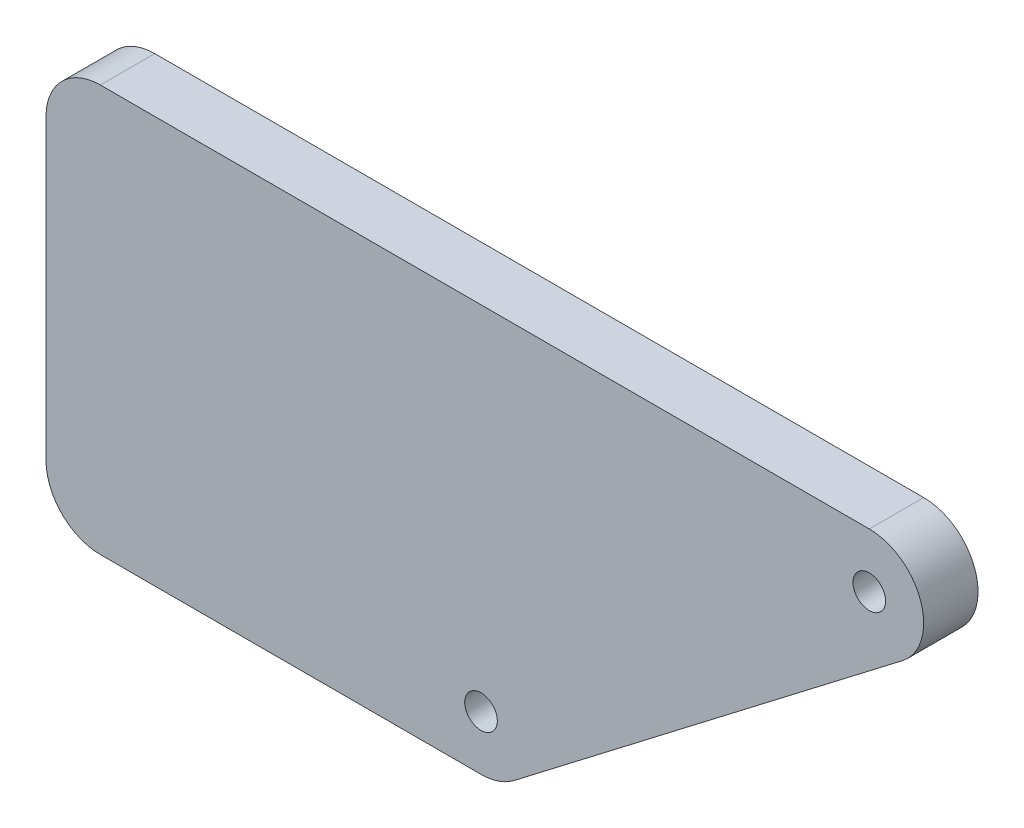
SolidWorks part; units mm, degrees
ref_plane "前视基准面" through (0, 0, 0) normal (0, 0, 1) x (1, 0, 0)
ref_plane "上视基准面" through (0, 0, 0) normal (0, 1, 0) x (1, 0, 0)
ref_plane "右视基准面" through (0, 0, 0) normal (1, 0, 0) x (0, 0, -1)
sketch "Sketch1" plane through (0, 0, 0) normal (0, 0, 1) x (1, 0, 0)
  line L0 (122.9511, -18.8201) -> (93.1268, -73.5554)
  line L1 (93.1268, -73.5554) -> (122.7846, -133.2618)
  line L2 (122.7846, -133.2618) -> (122.9511, -18.8201)
  line L3 (0, 0) -> (71.4018, 54.7885)
  line L4 (71.4018, 54.7885) -> (-333.3333, 54.7885)
  line L5 (-333.3333, 54.7885) -> (0, 0)
  line L6 (0, 0) -> (-333.3333, 54.7885)
  line L7 (-333.3333, 54.7885) -> (-333.3333, 0)
  line L8 (-333.3333, 0) -> (0, 0)
  line L9 (71.4018, 54.7885) -> (122.9511, -18.8201)
  line L10 (122.9511, -18.8201) -> (94.2741, 2.9429)
  line L11 (94.2741, 2.9429) -> (71.4018, 54.7885)
  line L12 (71.4018, 54.7885) -> (94.2741, 2.9429)
  line L13 (94.2741, 2.9429) -> (71.4018, 54.7885)
  line L14 (94.2741, 2.9429) -> (18.6205, -18.6205)
  line L15 (18.6205, -18.6205) -> (37.467, -41.2946)
  line L16 (37.467, -41.2946) -> (94.2741, 2.9429)
  line L17 (94.2741, 2.9429) -> (37.467, -41.2946)
  line L18 (37.467, -41.2946) -> (94.2741, 2.9429)
  line L19 (184.818, -172.2512) -> (184.6311, -172.3314)
  line L20 (184.6311, -172.3314) -> (184.444, -172.4113)
  line L21 (184.444, -172.4113) -> (184.2569, -172.4911)
  line L22 (184.2569, -172.4911) -> (184.0696, -172.5706)
  line L23 (184.0696, -172.5706) -> (183.8823, -172.6498)
  line L24 (183.8823, -172.6498) -> (183.6948, -172.7288)
  line L25 (183.6948, -172.7288) -> (183.5072, -172.8076)
  line L26 (183.5072, -172.8076) -> (183.3195, -172.8862)
  line L27 (183.3195, -172.8862) -> (183.1318, -172.9645)
  line L28 (183.1318, -172.9645) -> (182.9439, -173.0426)
  line L29 (182.9439, -173.0426) -> (182.7559, -173.1204)
  line L30 (182.7559, -173.1204) -> (182.5679, -173.198)
  line L31 (182.5679, -173.198) -> (182.3797, -173.2753)
  line L32 (182.3797, -173.2753) -> (182.1914, -173.3524)
  line L33 (182.1914, -173.3524) -> (182.003, -173.4293)
  line L34 (182.003, -173.4293) -> (181.8146, -173.5059)
  line L35 (181.8146, -173.5059) -> (181.626, -173.5823)
  line L36 (181.626, -173.5823) -> (181.4374, -173.6584)
  line L37 (181.4374, -173.6584) -> (181.2486, -173.7343)
  line L38 (181.2486, -173.7343) -> (181.0598, -173.8099)
  line L39 (181.0598, -173.8099) -> (180.8709, -173.8853)
  line L40 (180.8709, -173.8853) -> (180.6819, -173.9604)
  line L41 (180.6819, -173.9604) -> (180.4928, -174.0353)
  line L42 (180.4928, -174.0353) -> (180.3036, -174.11)
  line L43 (180.3036, -174.11) -> (180.1143, -174.1843)
  line L44 (180.1143, -174.1843) -> (179.9249, -174.2585)
  line L45 (179.9249, -174.2585) -> (179.7355, -174.3324)
  line L46 (179.7355, -174.3324) -> (179.546, -174.406)
  line L47 (179.546, -174.406) -> (179.3564, -174.4794)
  line L48 (179.3564, -174.4794) -> (179.1667, -174.5525)
  line L49 (179.1667, -174.5525) -> (178.9769, -174.6254)
  line L50 (178.9769, -174.6254) -> (178.7871, -174.698)
  line L51 (178.7871, -174.698) -> (178.5972, -174.7704)
  line L52 (178.5972, -174.7704) -> (178.4072, -174.8425)
  line L53 (178.4072, -174.8425) -> (178.2172, -174.9143)
  line L54 (178.2172, -174.9143) -> (178.027, -174.9859)
  line L55 (178.027, -174.9859) -> (177.8368, -175.0573)
  line L56 (177.8368, -175.0573) -> (177.6466, -175.1283)
  line L57 (177.6466, -175.1283) -> (177.4563, -175.1992)
  line L58 (177.4563, -175.1992) -> (177.2659, -175.2697)
  line L59 (177.2659, -175.2697) -> (177.0754, -175.34)
  line L60 (177.0754, -175.34) -> (176.8849, -175.41)
  line L61 (176.8849, -175.41) -> (176.6943, -175.4798)
  line L62 (176.6943, -175.4798) -> (176.5037, -175.5493)
  line L63 (176.5037, -175.5493) -> (176.313, -175.6186)
  line L64 (176.313, -175.6186) -> (176.1223, -175.6875)
  line L65 (176.1223, -175.6875) -> (175.9315, -175.7562)
  line L66 (175.9315, -175.7562) -> (175.7407, -175.8247)
  line L67 (175.7407, -175.8247) -> (175.5498, -175.8928)
  line L68 (175.5498, -175.8928) -> (175.3588, -175.9608)
  line L69 (175.3588, -175.9608) -> (175.1679, -176.0284)
  line L70 (175.1679, -176.0284) -> (174.9768, -176.0958)
  line L71 (174.9768, -176.0958) -> (174.7858, -176.1629)
  line L72 (174.7858, -176.1629) -> (174.5947, -176.2297)
  line L73 (174.5947, -176.2297) -> (174.4036, -176.2962)
  line L74 (174.4036, -176.2962) -> (174.2124, -176.3625)
  line L75 (174.2124, -176.3625) -> (174.0212, -176.4285)
  line L76 (174.0212, -176.4285) -> (173.8299, -176.4943)
  line L77 (173.8299, -176.4943) -> (173.6387, -176.5597)
  line L78 (173.6387, -176.5597) -> (173.4474, -176.6249)
  line L79 (173.4474, -176.6249) -> (173.2561, -176.6898)
  line L80 (173.2561, -176.6898) -> (173.0648, -176.7545)
  line L81 (173.0648, -176.7545) -> (172.8734, -176.8188)
  line L82 (172.8734, -176.8188) -> (172.682, -176.8829)
  line L83 (172.682, -176.8829) -> (172.4906, -176.9467)
  line L84 (172.4906, -176.9467) -> (172.2992, -177.0102)
  line L85 (172.2992, -177.0102) -> (172.1078, -177.0735)
  line L86 (172.1078, -177.0735) -> (171.9164, -177.1365)
  line L87 (171.9164, -177.1365) -> (171.725, -177.1991)
  line L88 (171.725, -177.1991) -> (171.5335, -177.2616)
  line L89 (171.5335, -177.2616) -> (171.3421, -177.3237)
  line L90 (171.3421, -177.3237) -> (171.1507, -177.3855)
  line L91 (171.1507, -177.3855) -> (170.9592, -177.4471)
  line L92 (170.9592, -177.4471) -> (170.7678, -177.5083)
  line L93 (170.7678, -177.5083) -> (170.5764, -177.5693)
  line L94 (170.5764, -177.5693) -> (170.385, -177.63)
  line L95 (170.385, -177.63) -> (170.1936, -177.6905)
  line L96 (170.1936, -177.6905) -> (170.0022, -177.7506)
  line L97 (170.0022, -177.7506) -> (169.8108, -177.8104)
  line L98 (169.8108, -177.8104) -> (169.6194, -177.87)
  line L99 (169.6194, -177.87) -> (169.4281, -177.9293)
  line L100 (169.4281, -177.9293) -> (169.2368, -177.9883)
  line L101 (169.2368, -177.9883) -> (169.0455, -178.047)
  line L102 (169.0455, -178.047) -> (168.8543, -178.1054)
  line L103 (168.8543, -178.1054) -> (168.6631, -178.1635)
  line L104 (168.6631, -178.1635) -> (168.4719, -178.2213)
  line L105 (168.4719, -178.2213) -> (168.2807, -178.2789)
  line L106 (168.2807, -178.2789) -> (168.0896, -178.3361)
  line L107 (168.0896, -178.3361) -> (167.8985, -178.3931)
  line L108 (167.8985, -178.3931) -> (167.7075, -178.4497)
  line L109 (167.7075, -178.4497) -> (167.5165, -178.5061)
  line L110 (167.5165, -178.5061) -> (167.3256, -178.5622)
  line L111 (167.3256, -178.5622) -> (167.1347, -178.618)
  line L112 (167.1347, -178.618) -> (166.9439, -178.6735)
  line L113 (166.9439, -178.6735) -> (166.7531, -178.7287)
  line L114 (166.7531, -178.7287) -> (166.5624, -178.7836)
  line L115 (166.5624, -178.7836) -> (166.3718, -178.8382)
  line L116 (166.3718, -178.8382) -> (166.1812, -178.8925)
  line L117 (166.1812, -178.8925) -> (165.9907, -178.9465)
  line L118 (165.9907, -178.9465) -> (165.8003, -179.0002)
  line L119 (165.8003, -179.0002) -> (165.6099, -179.0537)
  line L120 (165.6099, -179.0537) -> (165.4196, -179.1068)
  line L121 (165.4196, -179.1068) -> (165.2294, -179.1596)
  line L122 (165.2294, -179.1596) -> (165.0393, -179.2122)
  line L123 (165.0393, -179.2122) -> (164.8492, -179.2644)
  line L124 (164.8492, -179.2644) -> (164.6593, -179.3164)
  line L125 (164.6593, -179.3164) -> (164.4694, -179.368)
  line L126 (164.4694, -179.368) -> (164.2796, -179.4193)
  line L127 (164.2796, -179.4193) -> (164.09, -179.4704)
  line L128 (164.09, -179.4704) -> (163.9004, -179.5211)
  line L129 (163.9004, -179.5211) -> (163.7109, -179.5716)
  line L130 (163.7109, -179.5716) -> (163.5215, -179.6218)
  line L131 (163.5215, -179.6218) -> (163.3323, -179.6716)
  line L132 (163.3323, -179.6716) -> (163.1431, -179.7212)
  line L133 (163.1431, -179.7212) -> (162.9541, -179.7704)
  line L134 (162.9541, -179.7704) -> (162.7651, -179.8194)
  line L135 (162.7651, -179.8194) -> (162.5763, -179.868)
  line L136 (162.5763, -179.868) -> (162.3877, -179.9164)
  line L137 (162.3877, -179.9164) -> (162.1991, -179.9644)
  line L138 (162.1991, -179.9644) -> (162.0107, -180.0122)
  line L139 (162.0107, -180.0122) -> (161.8224, -180.0596)
  line L140 (161.8224, -180.0596) -> (161.6342, -180.1068)
  line L141 (161.6342, -180.1068) -> (161.4462, -180.1536)
  line L142 (161.4462, -180.1536) -> (161.2583, -180.2002)
  line L143 (161.2583, -180.2002) -> (161.0705, -180.2464)
  line L144 (161.0705, -180.2464) -> (160.8829, -180.2924)
  line L145 (160.8829, -180.2924) -> (160.6955, -180.338)
  line L146 (160.6955, -180.338) -> (160.5082, -180.3834)
  line L147 (160.5082, -180.3834) -> (160.321, -180.4284)
  line L148 (160.321, -180.4284) -> (160.134, -180.4732)
  line L149 (160.134, -180.4732) -> (159.9472, -180.5176)
  line L150 (159.9472, -180.5176) -> (159.7605, -180.5617)
  line L151 (159.7605, -180.5617) -> (159.574, -180.6056)
  line L152 (159.574, -180.6056) -> (159.3877, -180.6491)
  line L153 (159.3877, -180.6491) -> (159.2015, -180.6924)
  line L154 (159.2015, -180.6924) -> (159.0156, -180.7353)
  line L155 (159.0156, -180.7353) -> (158.8298, -180.7779)
  line L156 (158.8298, -180.7779) -> (158.6441, -180.8203)
  line L157 (158.6441, -180.8203) -> (158.4587, -180.8623)
  line L158 (158.4587, -180.8623) -> (158.2735, -180.904)
  line L159 (158.2735, -180.904) -> (158.0884, -180.9455)
  line L160 (158.0884, -180.9455) -> (157.9035, -180.9866)
  line L161 (157.9035, -180.9866) -> (157.7189, -181.0274)
  line L162 (157.7189, -181.0274) -> (157.5344, -181.068)
  line L163 (157.5344, -181.068) -> (157.3502, -181.1082)
  line L164 (157.3502, -181.1082) -> (157.1661, -181.1481)
  line L165 (157.1661, -181.1481) -> (156.9823, -181.1878)
  line L166 (156.9823, -181.1878) -> (156.7986, -181.2271)
  line L167 (156.7986, -181.2271) -> (156.6152, -181.2662)
  line L168 (156.6152, -181.2662) -> (156.432, -181.3049)
  line L169 (156.432, -181.3049) -> (156.249, -181.3433)
  line L170 (156.249, -181.3433) -> (156.0663, -181.3815)
  line L171 (156.0663, -181.3815) -> (155.8838, -181.4193)
  line L172 (155.8838, -181.4193) -> (155.7015, -181.4569)
  line L173 (155.7015, -181.4569) -> (155.5194, -181.4941)
  line L174 (155.5194, -181.4941) -> (155.3376, -181.5311)
  line L175 (155.3376, -181.5311) -> (155.156, -181.5678)
  line L176 (155.156, -181.5678) -> (154.9747, -181.6041)
  line L177 (154.9747, -181.6041) -> (154.7936, -181.6402)
  line L178 (154.7936, -181.6402) -> (154.6127, -181.676)
  line L179 (154.6127, -181.676) -> (154.4322, -181.7114)
  line L180 (154.4322, -181.7114) -> (154.2518, -181.7466)
  line L181 (154.2518, -181.7466) -> (154.0718, -181.7815)
  line L182 (154.0718, -181.7815) -> (153.892, -181.8161)
  line L183 (153.892, -181.8161) -> (153.7124, -181.8504)
  line L184 (153.7124, -181.8504) -> (153.5331, -181.8844)
  line L185 (153.5331, -181.8844) -> (153.3541, -181.9181)
  line L186 (153.3541, -181.9181) -> (153.1754, -181.9516)
  line L187 (153.1754, -181.9516) -> (152.9969, -181.9847)
  line L188 (152.9969, -181.9847) -> (152.8188, -182.0176)
  line L189 (152.8188, -182.0176) -> (152.6409, -182.0501)
  line L190 (152.6409, -182.0501) -> (152.4633, -182.0824)
  line L191 (152.4633, -182.0824) -> (152.286, -182.1144)
  line L192 (152.286, -182.1144) -> (152.109, -182.1461)
  line L193 (152.109, -182.1461) -> (151.9322, -182.1775)
  line L194 (151.9322, -182.1775) -> (151.7558, -182.2086)
  line L195 (151.7558, -182.2086) -> (151.5797, -182.2394)
  line L196 (151.5797, -182.2394) -> (151.4039, -182.27)
  line L197 (151.4039, -182.27) -> (151.2284, -182.3002)
  line L198 (151.2284, -182.3002) -> (151.0532, -182.3302)
  line L199 (151.0532, -182.3302) -> (150.8783, -182.3599)
  line L200 (150.8783, -182.3599) -> (150.7037, -182.3893)
  line L201 (150.7037, -182.3893) -> (150.5295, -182.4184)
  line L202 (150.5295, -182.4184) -> (150.3555, -182.4473)
  line L203 (150.3555, -182.4473) -> (150.1819, -182.4758)
  line L204 (150.1819, -182.4758) -> (150.0087, -182.5041)
  line L205 (150.0087, -182.5041) -> (149.8357, -182.5321)
  line L206 (149.8357, -182.5321) -> (149.6631, -182.5598)
  line L207 (149.6631, -182.5598) -> (149.4908, -182.5873)
  line L208 (149.4908, -182.5873) -> (149.3189, -182.6145)
  line L209 (149.3189, -182.6145) -> (149.1473, -182.6413)
  line L210 (149.1473, -182.6413) -> (148.9761, -182.668)
  line L211 (148.9761, -182.668) -> (148.8052, -182.6943)
  line L212 (148.8052, -182.6943) -> (148.6347, -182.7204)
  line L213 (148.6347, -182.7204) -> (148.4645, -182.7462)
  line L214 (148.4645, -182.7462) -> (148.2946, -182.7717)
  line L215 (148.2946, -182.7717) -> (148.1252, -182.797)
  line L216 (148.1252, -182.797) -> (147.9561, -182.8219)
  line L217 (147.9561, -182.8219) -> (147.7873, -182.8467)
  line L218 (147.7873, -182.8467) -> (147.619, -182.8711)
  line L219 (147.619, -182.8711) -> (147.451, -182.8953)
  line L220 (147.451, -182.8953) -> (147.2833, -182.9192)
  line L221 (147.2833, -182.9192) -> (147.1161, -182.9429)
  line L222 (147.1161, -182.9429) -> (146.9492, -182.9662)
  line L223 (146.9492, -182.9662) -> (146.7827, -182.9894)
  line L224 (146.7827, -182.9894) -> (146.6166, -183.0122)
  line L225 (146.6166, -183.0122) -> (146.4509, -183.0348)
  line L226 (146.4509, -183.0348) -> (146.2856, -183.0571)
  line L227 (146.2856, -183.0571) -> (146.1206, -183.0792)
  line L228 (146.1206, -183.0792) -> (145.9561, -183.101)
  line L229 (145.9561, -183.101) -> (145.7919, -183.1226)
  line L230 (145.7919, -183.1226) -> (145.6282, -183.1439)
  line L231 (145.6282, -183.1439) -> (145.4649, -183.165)
  line L232 (145.4649, -183.165) -> (145.3019, -183.1858)
  line L233 (145.3019, -183.1858) -> (145.1394, -183.2063)
  line L234 (145.1394, -183.2063) -> (144.9773, -183.2266)
  line L235 (144.9773, -183.2266) -> (144.8156, -183.2466)
  line L236 (144.8156, -183.2466) -> (144.6543, -183.2664)
  line L237 (144.6543, -183.2664) -> (144.4934, -183.286)
  line L238 (144.4934, -183.286) -> (144.3329, -183.3053)
  line L239 (144.3329, -183.3053) -> (144.1729, -183.3243)
  line L240 (144.1729, -183.3243) -> (144.0133, -183.3431)
  line L241 (144.0133, -183.3431) -> (143.8541, -183.3617)
  line L242 (143.8541, -183.3617) -> (143.6953, -183.38)
  line L243 (143.6953, -183.38) -> (143.537, -183.3981)
  line L244 (143.537, -183.3981) -> (143.3791, -183.4159)
  line L245 (143.3791, -183.4159) -> (143.2217, -183.4335)
  line L246 (143.2217, -183.4335) -> (143.0646, -183.4508)
  line L247 (143.0646, -183.4508) -> (142.908, -183.468)
  line L248 (142.908, -183.468) -> (142.7519, -183.4849)
  line L249 (142.7519, -183.4849) -> (142.5962, -183.5015)
  line L250 (142.5962, -183.5015) -> (142.4409, -183.5179)
  line L251 (142.4409, -183.5179) -> (142.2861, -183.5341)
  line L252 (142.2861, -183.5341) -> (142.1318, -183.5501)
  line L253 (142.1318, -183.5501) -> (141.9778, -183.5658)
  line L254 (141.9778, -183.5658) -> (141.8244, -183.5813)
  line L255 (141.8244, -183.5813) -> (141.6714, -183.5966)
  line L256 (141.6714, -183.5966) -> (141.5188, -183.6116)
  line L257 (141.5188, -183.6116) -> (141.3667, -183.6265)
  line L258 (141.3667, -183.6265) -> (141.2151, -183.6411)
  line L259 (141.2151, -183.6411) -> (141.0639, -183.6554)
  line L260 (141.0639, -183.6554) -> (140.9132, -183.6696)
  line L261 (140.9132, -183.6696) -> (140.7629, -183.6836)
  line L262 (140.7629, -183.6836) -> (140.6132, -183.6973)
  line L263 (140.6132, -183.6973) -> (140.4638, -183.7108)
  line L264 (140.4638, -183.7108) -> (140.315, -183.7241)
  line L265 (140.315, -183.7241) -> (140.1666, -183.7372)
  line L266 (140.1666, -183.7372) -> (140.0187, -183.7501)
  line L267 (140.0187, -183.7501) -> (139.8713, -183.7627)
  line L268 (139.8713, -183.7627) -> (139.7243, -183.7752)
  line L269 (139.7243, -183.7752) -> (139.5778, -183.7874)
  line L270 (139.5778, -183.7874) -> (139.4318, -183.7995)
  line L271 (139.4318, -183.7995) -> (139.2863, -183.8113)
  line L272 (139.2863, -183.8113) -> (139.1412, -183.823)
  line L273 (139.1412, -183.823) -> (138.9966, -183.8344)
  line L274 (138.9966, -183.8344) -> (138.8525, -183.8456)
  line L275 (138.8525, -183.8456) -> (138.7089, -183.8567)
  line L276 (138.7089, -183.8567) -> (138.5658, -183.8675)
  line L277 (138.5658, -183.8675) -> (138.4231, -183.8781)
  line L278 (138.4231, -183.8781) -> (138.2809, -183.8886)
  line L279 (138.2809, -183.8886) -> (138.1393, -183.8988)
  line L280 (138.1393, -183.8988) -> (137.998, -183.9089)
  line L281 (137.998, -183.9089) -> (137.8573, -183.9188)
  line L282 (137.8573, -183.9188) -> (137.7171, -183.9285)
  line L283 (137.7171, -183.9285) -> (137.5773, -183.938)
  line L284 (137.5773, -183.938) -> (137.4381, -183.9473)
  line L285 (137.4381, -183.9473) -> (137.2993, -183.9564)
  line L286 (137.2993, -183.9564) -> (137.161, -183.9654)
  line L287 (137.161, -183.9654) -> (137.0232, -183.9741)
  line L288 (137.0232, -183.9741) -> (136.8859, -183.9827)
  line L289 (136.8859, -183.9827) -> (136.7491, -183.9911)
  line L290 (136.7491, -183.9911) -> (136.6127, -183.9994)
  line L291 (136.6127, -183.9994) -> (136.4769, -184.0074)
  line L292 (136.4769, -184.0074) -> (136.3415, -184.0153)
  line L293 (136.3415, -184.0153) -> (136.2066, -184.023)
  line L294 (136.2066, -184.023) -> (136.0722, -184.0306)
  line L295 (136.0722, -184.0306) -> (135.9383, -184.0379)
  line L296 (135.9383, -184.0379) -> (135.8049, -184.0451)
  line L297 (135.8049, -184.0451) -> (135.672, -184.0522)
  line L298 (135.672, -184.0522) -> (135.5395, -184.0591)
  line L299 (135.5395, -184.0591) -> (135.4075, -184.0658)
  line L300 (135.4075, -184.0658) -> (135.276, -184.0723)
  line L301 (135.276, -184.0723) -> (135.145, -184.0787)
  line L302 (135.145, -184.0787) -> (135.0145, -184.0849)
  line L303 (135.0145, -184.0849) -> (134.8845, -184.091)
  line L304 (134.8845, -184.091) -> (134.7549, -184.0969)
  line L305 (134.7549, -184.0969) -> (134.6258, -184.1027)
  line L306 (134.6258, -184.1027) -> (134.4972, -184.1083)
  line L307 (134.4972, -184.1083) -> (134.3691, -184.1137)
  line L308 (134.3691, -184.1137) -> (134.2414, -184.119)
  line L309 (134.2414, -184.119) -> (134.1142, -184.1242)
  line L310 (134.1142, -184.1242) -> (133.9875, -184.1292)
  line L311 (133.9875, -184.1292) -> (133.8613, -184.1341)
  line L312 (133.8613, -184.1341) -> (133.7355, -184.1388)
  line L313 (133.7355, -184.1388) -> (133.6102, -184.1434)
  line L314 (133.6102, -184.1434) -> (133.4853, -184.1478)
  line L315 (133.4853, -184.1478) -> (133.3609, -184.1521)
  line L316 (133.3609, -184.1521) -> (133.237, -184.1563)
  line L317 (133.237, -184.1563) -> (133.1135, -184.1603)
  line L318 (133.1135, -184.1603) -> (132.9905, -184.1642)
  line L319 (132.9905, -184.1642) -> (132.8679, -184.1679)
  line L320 (132.8679, -184.1679) -> (132.7458, -184.1715)
  line L321 (132.7458, -184.1715) -> (132.6242, -184.175)
  line L322 (132.6242, -184.175) -> (132.5029, -184.1784)
  line L323 (132.5029, -184.1784) -> (132.3821, -184.1816)
  line L324 (132.3821, -184.1816) -> (132.2618, -184.1847)
  line L325 (132.2618, -184.1847) -> (132.1419, -184.1877)
  line L326 (132.1419, -184.1877) -> (132.0224, -184.1905)
  line L327 (132.0224, -184.1905) -> (131.9033, -184.1933)
  line L328 (131.9033, -184.1933) -> (131.7847, -184.1959)
  line L329 (131.7847, -184.1959) -> (131.6665, -184.1983)
  line L330 (131.6665, -184.1983) -> (131.5487, -184.2007)
  line L331 (131.5487, -184.2007) -> (131.4313, -184.2029)
  line L332 (131.4313, -184.2029) -> (131.3144, -184.2051)
  line L333 (131.3144, -184.2051) -> (131.1978, -184.2071)
  line L334 (131.1978, -184.2071) -> (131.0816, -184.209)
  line L335 (131.0816, -184.209) -> (130.9658, -184.2107)
  line L336 (130.9658, -184.2107) -> (130.8505, -184.2124)
  line L337 (130.8505, -184.2124) -> (130.7355, -184.214)
  line L338 (130.7355, -184.214) -> (130.6209, -184.2154)
  line L339 (130.6209, -184.2154) -> (130.5066, -184.2168)
  line L340 (130.5066, -184.2168) -> (130.3927, -184.218)
  line L341 (130.3927, -184.218) -> (130.2792, -184.2191)
  line L342 (130.2792, -184.2191) -> (130.1661, -184.2201)
  line L343 (130.1661, -184.2201) -> (130.0533, -184.221)
  line L344 (130.0533, -184.221) -> (129.9409, -184.2219)
  line L345 (129.9409, -184.2219) -> (129.8288, -184.2226)
  line L346 (129.8288, -184.2226) -> (129.717, -184.2232)
  line L347 (129.717, -184.2232) -> (129.6056, -184.2237)
  line L348 (129.6056, -184.2237) -> (129.4945, -184.2241)
  line L349 (129.4945, -184.2241) -> (129.3837, -184.2244)
  line L350 (129.3837, -184.2244) -> (129.2732, -184.2246)
  line L351 (129.2732, -184.2246) -> (129.163, -184.2247)
  line L352 (129.163, -184.2247) -> (129.0531, -184.2248)
  line L353 (129.0531, -184.2248) -> (128.9435, -184.2247)
  line L354 (128.9435, -184.2247) -> (128.8342, -184.2245)
  line L355 (128.8342, -184.2245) -> (128.7251, -184.2243)
  line L356 (128.7251, -184.2243) -> (128.6163, -184.2239)
  line L357 (128.6163, -184.2239) -> (128.5078, -184.2235)
  line L358 (128.5078, -184.2235) -> (128.3995, -184.223)
  line L359 (128.3995, -184.223) -> (128.2915, -184.2223)
  line L360 (128.2915, -184.2223) -> (128.1836, -184.2216)
  line L361 (128.1836, -184.2216) -> (128.076, -184.2208)
  line L362 (128.076, -184.2208) -> (127.9686, -184.22)
  line L363 (127.9686, -184.22) -> (127.8615, -184.219)
  line L364 (127.8615, -184.219) -> (127.7544, -184.2179)
  line L365 (127.7544, -184.2179) -> (127.6476, -184.2168)
  line L366 (127.6476, -184.2168) -> (127.541, -184.2156)
  line L367 (127.541, -184.2156) -> (127.4345, -184.2143)
  line L368 (127.4345, -184.2143) -> (127.3281, -184.2129)
  line L369 (127.3281, -184.2129) -> (127.2219, -184.2114)
  line L370 (127.2219, -184.2114) -> (127.1158, -184.2098)
  line L371 (127.1158, -184.2098) -> (127.0099, -184.2082)
  line L372 (127.0099, -184.2082) -> (126.904, -184.2065)
  line L373 (126.904, -184.2065) -> (126.7982, -184.2047)
  line L374 (126.7982, -184.2047) -> (126.6925, -184.2028)
  line L375 (126.6925, -184.2028) -> (126.5868, -184.2008)
  line L376 (126.5868, -184.2008) -> (126.4813, -184.1988)
  line L377 (126.4813, -184.1988) -> (126.3757, -184.1966)
  line L378 (126.3757, -184.1966) -> (126.2702, -184.1944)
  line L379 (126.2702, -184.1944) -> (126.1646, -184.1922)
  line L380 (126.1646, -184.1922) -> (126.0591, -184.1898)
  line L381 (126.0591, -184.1898) -> (125.9535, -184.1873)
  line L382 (125.9535, -184.1873) -> (125.848, -184.1848)
  line L383 (125.848, -184.1848) -> (125.7423, -184.1822)
  line L384 (125.7423, -184.1822) -> (125.6366, -184.1795)
  line L385 (125.6366, -184.1795) -> (125.5308, -184.1767)
  line L386 (125.5308, -184.1767) -> (125.4249, -184.1739)
  line L387 (125.4249, -184.1739) -> (125.3189, -184.171)
  line L388 (125.3189, -184.171) -> (125.2128, -184.168)
  line L389 (125.2128, -184.168) -> (125.1065, -184.1649)
  line L390 (125.1065, -184.1649) -> (125, -184.1617)
  line L391 (125, -184.1617) -> (124.8933, -184.1584)
  line L392 (124.8933, -184.1584) -> (124.7865, -184.1551)
  line L393 (124.7865, -184.1551) -> (124.6794, -184.1517)
  line L394 (124.6794, -184.1517) -> (124.572, -184.1482)
  line L395 (124.572, -184.1482) -> (124.4644, -184.1446)
  line L396 (124.4644, -184.1446) -> (124.3565, -184.1409)
  line L397 (124.3565, -184.1409) -> (124.2483, -184.1372)
  line L398 (124.2483, -184.1372) -> (124.1397, -184.1333)
  line L399 (124.1397, -184.1333) -> (124.0308, -184.1294)
  line L400 (124.0308, -184.1294) -> (123.9215, -184.1254)
  line L401 (123.9215, -184.1254) -> (123.8118, -184.1213)
  line L402 (123.8118, -184.1213) -> (123.7017, -184.1171)
  line L403 (123.7017, -184.1171) -> (123.5911, -184.1128)
  line L404 (123.5911, -184.1128) -> (123.4801, -184.1084)
  line L405 (123.4801, -184.1084) -> (123.3685, -184.1039)
  line L406 (123.3685, -184.1039) -> (123.2564, -184.0994)
  line L407 (123.2564, -184.0994) -> (123.1438, -184.0947)
  line L408 (123.1438, -184.0947) -> (123.0306, -184.0899)
  line L409 (123.0306, -184.0899) -> (122.9167, -184.0851)
  line L410 (122.9167, -184.0851) -> (122.8022, -184.0801)
  line L411 (122.8022, -184.0801) -> (122.6871, -184.075)
  line L412 (122.6871, -184.075) -> (122.5712, -184.0699)
  line L413 (122.5712, -184.0699) -> (122.4547, -184.0646)
  line L414 (122.4547, -184.0646) -> (122.3373, -184.0592)
  line L415 (122.3373, -184.0592) -> (122.2192, -184.0537)
  line L416 (122.2192, -184.0537) -> (122.1002, -184.0481)
  line L417 (122.1002, -184.0481) -> (121.9804, -184.0424)
  line L418 (121.9804, -184.0424) -> (121.8596, -184.0366)
  line L419 (121.8596, -184.0366) -> (121.7379, -184.0306)
  line L420 (121.7379, -184.0306) -> (121.6153, -184.0245)
  line L421 (121.6153, -184.0245) -> (121.4916, -184.0183)
  line L422 (121.4916, -184.0183) -> (121.3669, -184.012)
  line L423 (121.3669, -184.012) -> (121.2411, -184.0055)
  line L424 (121.2411, -184.0055) -> (121.1142, -183.9989)
  line L425 (121.1142, -183.9989) -> (120.9861, -183.9922)
  line L426 (120.9861, -183.9922) -> (120.8568, -183.9854)
  line L427 (120.8568, -183.9854) -> (120.7262, -183.9784)
  line L428 (120.7262, -183.9784) -> (120.5944, -183.9712)
  line L429 (120.5944, -183.9712) -> (120.4612, -183.9639)
  line L430 (120.4612, -183.9639) -> (120.3266, -183.9565)
  line L431 (120.3266, -183.9565) -> (120.1905, -183.9488)
  line L432 (120.1905, -183.9488) -> (120.053, -183.9411)
  line L433 (120.053, -183.9411) -> (119.9139, -183.9332)
  line L434 (119.9139, -183.9332) -> (119.7732, -183.9251)
  line L435 (119.7732, -183.9251) -> (119.6309, -183.9168)
  line L436 (119.6309, -183.9168) -> (119.4869, -183.9083)
  line L437 (119.4869, -183.9083) -> (119.3411, -183.8997)
  line L438 (119.3411, -183.8997) -> (119.1935, -183.8909)
  line L439 (119.1935, -183.8909) -> (119.044, -183.8819)
  line L440 (119.044, -183.8819) -> (118.8926, -183.8727)
  line L441 (118.8926, -183.8727) -> (118.7392, -183.8633)
  line L442 (118.7392, -183.8633) -> (118.5837, -183.8537)
  line L443 (118.5837, -183.8537) -> (118.4262, -183.8439)
  line L444 (118.4262, -183.8439) -> (118.2664, -183.8338)
  line L445 (118.2664, -183.8338) -> (118.1043, -183.8236)
  line L446 (118.1043, -183.8236) -> (117.9399, -183.8131)
  line L447 (117.9399, -183.8131) -> (117.7732, -183.8023)
  line L448 (117.7732, -183.8023) -> (117.6039, -183.7914)
  line L449 (117.6039, -183.7914) -> (117.4321, -183.7801)
  line L450 (117.4321, -183.7801) -> (117.2576, -183.7687)
  line L451 (117.2576, -183.7687) -> (117.0804, -183.7569)
  line L452 (117.0804, -183.7569) -> (116.9004, -183.7449)
  line L453 (116.9004, -183.7449) -> (116.7175, -183.7326)
  line L454 (116.7175, -183.7326) -> (116.5317, -183.72)
  line L455 (116.5317, -183.72) -> (116.3428, -183.7072)
  line L456 (116.3428, -183.7072) -> (116.1507, -183.694)
  line L457 (116.1507, -183.694) -> (115.9553, -183.6805)
  line L458 (115.9553, -183.6805) -> (115.7566, -183.6667)
  line L459 (115.7566, -183.6667) -> (115.5545, -183.6525)
  line L460 (115.5545, -183.6525) -> (115.3487, -183.638)
  line L461 (115.3487, -183.638) -> (115.1393, -183.6232)
  line L462 (115.1393, -183.6232) -> (114.9261, -183.608)
  line L463 (114.9261, -183.608) -> (114.709, -183.5924)
  line L464 (114.709, -183.5924) -> (114.4879, -183.5764)
  line L465 (114.4879, -183.5764) -> (114.2627, -183.5601)
  line L466 (114.2627, -183.5601) -> (114.0331, -183.5433)
  line L467 (114.0331, -183.5433) -> (113.7992, -183.5261)
  line L468 (113.7992, -183.5261) -> (113.5608, -183.5085)
  line L469 (113.5608, -183.5085) -> (113.3176, -183.4905)
  line L470 (113.3176, -183.4905) -> (113.0697, -183.4719)
  line L471 (113.0697, -183.4719) -> (112.8168, -183.4529)
  line L472 (112.8168, -183.4529) -> (112.5588, -183.4335)
  line L473 (112.5588, -183.4335) -> (112.2955, -183.4135)
  line L474 (112.2955, -183.4135) -> (112.0268, -183.393)
  line L475 (112.0268, -183.393) -> (111.7525, -183.372)
  line L476 (111.7525, -183.372) -> (111.4724, -183.3504)
  line L477 (111.4724, -183.3504) -> (111.1863, -183.3282)
  line L478 (111.1863, -183.3282) -> (110.8942, -183.3055)
  line L479 (110.8942, -183.3055) -> (110.5956, -183.2821)
  line L480 (110.5956, -183.2821) -> (110.2906, -183.2582)
  line L481 (110.2906, -183.2582) -> (109.9788, -183.2335)
  line L482 (109.9788, -183.2335) -> (109.6601, -183.2083)
  line L483 (109.6601, -183.2083) -> (109.3343, -183.1823)
  line L484 (109.3343, -183.1823) -> (109.001, -183.1556)
  line L485 (109.001, -183.1556) -> (108.6601, -183.1282)
  line L486 (108.6601, -183.1282) -> (108.3113, -183.1001)
  line L487 (108.3113, -183.1001) -> (107.9544, -183.0711)
  line L488 (107.9544, -183.0711) -> (107.5891, -183.0414)
  line L489 (107.5891, -183.0414) -> (107.2151, -183.0108)
  line L490 (107.2151, -183.0108) -> (106.8322, -182.9794)
  line L491 (106.8322, -182.9794) -> (106.4401, -182.9471)
  line L492 (106.4401, -182.9471) -> (106.0384, -182.9138)
  line L493 (106.0384, -182.9138) -> (105.6268, -182.8796)
  line L494 (105.6268, -182.8796) -> (105.2051, -182.8445)
  line L495 (105.2051, -182.8445) -> (104.7728, -182.8083)
  line L496 (104.7728, -182.8083) -> (104.3296, -182.7711)
  line L497 (104.3296, -182.7711) -> (103.8751, -182.7327)
  line L498 (103.8751, -182.7327) -> (103.409, -182.6933)
  line L499 (103.409, -182.6933) -> (102.9308, -182.6527)
  line L500 (102.9308, -182.6527) -> (102.4402, -182.6108)
  line L501 (102.4402, -182.6108) -> (101.9366, -182.5678)
  line L502 (101.9366, -182.5678) -> (101.4196, -182.5234)
  line L503 (101.4196, -182.5234) -> (100.8889, -182.4777)
  line L504 (100.8889, -182.4777) -> (100.3437, -182.4306)
  line L505 (100.3437, -182.4306) -> (99.7837, -182.3821)
  line L506 (99.7837, -182.3821) -> (99.2083, -182.332)
  line L507 (99.2083, -182.332) -> (98.6169, -182.2804)
  line L508 (98.6169, -182.2804) -> (98.009, -182.2272)
  line L509 (98.009, -182.2272) -> (97.3838, -182.1724)
  line L510 (97.3838, -182.1724) -> (96.7409, -182.1158)
  line L511 (96.7409, -182.1158) -> (96.0794, -182.0574)
  line L512 (96.0794, -182.0574) -> (95.3986, -181.9971)
  line L513 (95.3986, -181.9971) -> (94.698, -181.9349)
  line L514 (94.698, -181.9349) -> (93.9765, -181.8706)
  line L515 (93.9765, -181.8706) -> (93.2334, -181.8043)
  line L516 (93.2334, -181.8043) -> (92.468, -181.7357)
  line L517 (92.468, -181.7357) -> (91.6791, -181.6649)
  line L518 (0, 0) -> (71.4018, 54.7885)
  line L519 (0, 0) -> (18.6205, -18.6205)
  line L520 (93.1268, -73.5554) -> (37.467, -41.2946)
  line L521 (122.9511, -18.8201) -> (93.1268, -73.5554)
curve "Curve1"
sketch "Sketch2" plane through (0, 0, 0) normal (0, 0, 1) x (1, 0, 0)
  line L0 (-70, 54.7885) -> (-70, 0) construction
  line L1 (-70, 64.7885) -> (71.4018, 64.7885)
  line L2 (-80, 54.7885) -> (-80, 0)
  line L3 (-70, -10) -> (0, -10)
  line L4 (77.4894, 46.855) -> (6.0876, -7.9335)
  line L510 (71.4018, 54.7885) -> (-333.3333, 54.7885) construction
  line L514 (-333.3333, 0) -> (0, 0) construction
  line L517 (0, 0) -> (71.4018, 54.7885) construction
  line L1032 (71.4018, 54.7885) -> (-70, 54.7885) construction
  line L1036 (-70, 0) -> (0, 0) construction
  line L1039 (0, 0) -> (71.4018, 54.7885) construction
  circle A0 centre (71.4018, 54.7885) radius 3
  circle A1 centre (0, 0) radius 10
  circle A2 centre (0, 0) radius 3
  circle A3 centre (71.4018, 54.7885) radius 10
  circle A4 centre (-70, 54.7885) radius 10
  circle A5 centre (-70, 0) radius 10
  point P16 (0, -5)
  dimension "D2" = 20
  dimension "D3" = 6
  dimension "D1" = 70
extrude "Extrude1" add sketch "Sketch2" along normal blind 10 contours A5 L3 A1 L4 A3 L1 A4 L2 | A1 A2 | A5 | A4 | A3 A0
